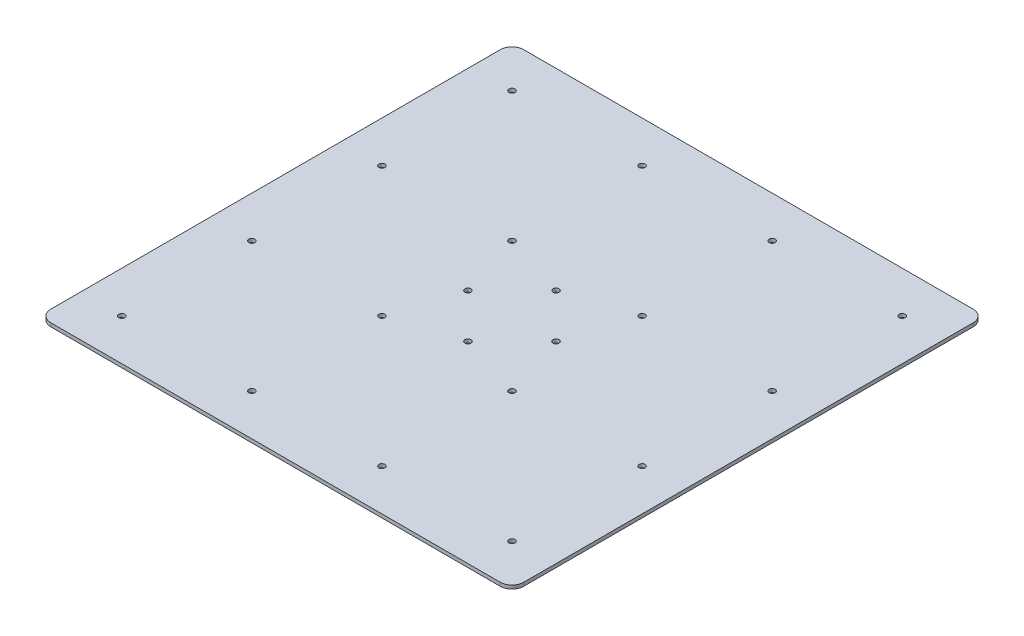
SolidWorks part; units mm, degrees
material "Stainless Steel (ferritic)"
ref_plane "Front Plane" through (0, 0, 0) normal (0, 0, 1) x (1, 0, 0)
ref_plane "Top Plane" through (0, 0, 0) normal (0, 1, 0) x (1, 0, 0)
ref_plane "Right Plane" through (0, 0, 0) normal (1, 0, 0) x (0, 0, -1)
sketch "Sketch1" plane through (0, 0, 0) normal (0, 1, 0) x (1, 0, 0)
  line L1 (-200, 200) -> (200, 200)
  line L2 (-200, 200) -> (-200, -200)
  line L3 (-200, -200) -> (200, -200)
  line L4 (200, 200) -> (200, -200)
  line L5 (-200, 200) -> (200, -200) construction
  line L6 (-200, -200) -> (200, 200) construction
  point P0 (0, 0)
  dimension "D1" = 400
  dimension "D2" = 400
extrude "Boss-Extrude1" add sketch "Sketch1" along normal blind 3
sketch "Sketch3" plane through (0, 3, 0) normal (0, 1, 0) x (1, 0, 0)
  line L0 (0, 0) -> (-37.25, 0) construction
  line L1 (-19.25, 20.25) -> (19.25, 20.25)
  line L2 (-20.25, 19.25) -> (-20.25, -19.25)
  line L3 (-19.25, -20.25) -> (19.25, -20.25)
  line L4 (20.25, 19.25) -> (20.25, -19.25)
  line L5 (-20.25, 20.25) -> (20.25, -20.25) construction
  line L6 (-20.25, -20.25) -> (20.25, 20.25) construction
  line L7 (0, 0) -> (-37.25, 0) construction
  line L8 (0, 0) -> (0, 37.25) construction
  arc A0 (-20.25, -19.25) -> (-19.25, -20.25) centre (-19.25, -19.25) ccw
  arc A1 (19.25, -20.25) -> (20.25, -19.25) centre (19.25, -19.25) ccw
  arc A2 (19.25, 20.25) -> (20.25, 19.25) centre (19.25, 19.25) cw
  arc A3 (-19.25, 20.25) -> (-20.25, 19.25) centre (-19.25, 19.25) ccw
  circle A4 centre (-37.25, 0) radius 2.58
  circle A5 centre (0, 37.25) radius 2.58
  circle A6 centre (37.25, 0) radius 2.58
  circle A7 centre (0, -37.25) radius 2.58
  point P0 (0, 0)
  point P21 (-20.25, 0)
  dimension "D3" = 1
  dimension "D4" = 5.16
  dimension "D1" = 40.5
  dimension "D2" = 40.5
  dimension "D5" = 17
  dimension "D7" = 90
  dimension "D8" = 37.25
  dimension "D6" = 4
extrude "Cut-Extrude1" cut sketch "Sketch3" against normal through all contours A7 | A4 | A5 | A6
sketch "Sketch4" plane through (0, 3, 0) normal (0, 1, 0) x (1, 0, 0)
  line L0 (-165, 165) -> (-200, 165) construction
  line L1 (-200, 200) -> (-200, -200) construction
  line L2 (-165, 165) -> (-165, 200) construction
  line L3 (200, 200) -> (-200, 200) construction
  line L4 (-165, 165) -> (-55, 165) construction
  line L5 (-165, 165) -> (-165, 55) construction
  circle A0 centre (-165, 165) radius 2.58
  circle A1 centre (-55, 165) radius 2.58
  circle A2 centre (55, 165) radius 2.58
  circle A3 centre (165, 165) radius 2.58
  circle A4 centre (-55, 55) radius 2.58
  circle A5 centre (55, 55) radius 2.58
  circle A6 centre (165, 55) radius 2.58
  circle A7 centre (-55, -55) radius 2.58
  circle A8 centre (55, -55) radius 2.58
  circle A9 centre (165, -55) radius 2.58
  circle A10 centre (-55, -165) radius 2.58
  circle A11 centre (55, -165) radius 2.58
  circle A12 centre (165, -165) radius 2.58
  circle A13 centre (-165, 55) radius 2.58
  circle A14 centre (-165, -55) radius 2.58
  circle A15 centre (-165, -165) radius 2.58
  dimension "D2" = 5.16
  dimension "D1" = 35
  dimension "D5" = 90
  dimension "D6" = 110
  dimension "D7" = 110
  dimension "D3" = 4
  dimension "D4" = 4
extrude "Cut-Extrude2" cut sketch "Sketch4" against normal through all
fillet "Fillet1" radius 10 4 edges at (-200, 1.5, 200) (200, 1.5, 200) (200, 1.5, -200) (-200, 1.5, -200)
